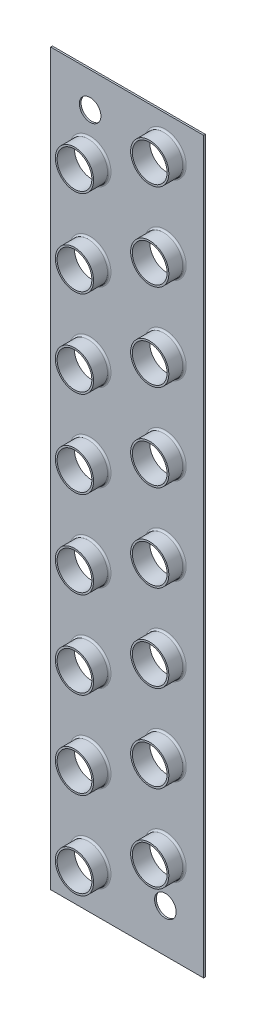
SolidWorks part; units mm, degrees
ref_plane "Front Plane" through (0, 0, 0) normal (0, 0, 1) x (1, 0, 0)
ref_plane "Top Plane" through (0, 0, 0) normal (0, 1, 0) x (1, 0, 0)
ref_plane "Right Plane" through (0, 0, 0) normal (1, 0, 0) x (0, 0, -1)
sketch "Sketch2" plane through (0, 0, 0) normal (0, 0, 1) x (1, 0, 0)
  line L1 (0, 0) -> (44, 0)
  line L2 (0, 0) -> (0, -210)
  line L3 (0, -210) -> (44, -210)
  line L4 (44, 0) -> (44, -210)
  dimension "D1" = 44
  dimension "D2" = 210
extrude "Boss-Extrude1" add sketch "Sketch2" along normal blind 0.5
sketch "Sketch3" plane through (0, 0, 0.5) normal (0, 0, 1) x (1, 0, 0)
  line L0 (44, 0) -> (0, 0) construction
  line L2 (11.3494, -22.5) -> (33, -22.5) construction
  line L3 (22.1747, -22.5) -> (22.1747, -34.2411) construction
  circle A0 centre (33, -10) radius 5
  circle A1 centre (11.3494, -22.5) radius 5
  point P11 (0, 0)
  point P12 (0, 0)
  point P13 (0, 0)
  point P14 (0, 0)
  dimension "D1" = 10
  dimension "D2" = 10
  dimension "D3" = 10
  dimension "D4" = 12.5
  dimension "D5" = 25
extrude "Cut-Extrude1" cut sketch "Sketch3" against normal through all
sketch "Sketch4" plane through (0, 0, 0.5) normal (0, 0, 1) x (1, 0, 0)
  circle A0 centre (11.3494, -22.5) radius 5.5
  circle A1 centre (11.3494, -22.5) radius 5
  circle A2 centre (11.3494, -22.5) radius 5
  circle A3 centre (33, -10) radius 5
  circle A4 centre (33, -10) radius 5
  circle A5 centre (33, -10) radius 5.5
  dimension "D1" = 0
  dimension "D2" = 0
  dimension "D3" = 0.5
extrude "Boss-Extrude2" add sketch "Sketch4" along normal blind 4.5
pattern_linear "LPattern1" count 8 spacing 25 along (0, -1, 0) of "Boss-Extrude2", "Cut-Extrude1"
fillet "Fillet1" radius 0.5 16 edges at (38.5, -10, 0.5) (16.8494, -22.5, 0.5) (38.5, -185, 0.5) (16.8494, -197.5, 0.5) (16.8494, -172.5, 0.5) (38.5, -160, 0.5) (16.8494, -147.5, 0.5) (38.5, -135, 0.5) (16.8494, -122.5, 0.5) (38.5, -110, 0.5) (16.8494, -97.5, 0.5) (38.5, -85, 0.5) (16.8494, -72.5, 0.5) (38.5, -60, 0.5) (38.5, -35, 0.5) (16.8494, -47.5, 0.5)
sketch "Sketch5" plane through (0, 0, 0) normal (0, 0, -1) x (-1, 0, 0)
  line L0 (-11.3494, -10) -> (-11.3494, -22.5) construction
  line L1 (-11.3494, -10) -> (-33, -10) construction
  line L2 (-33, -197.5) -> (-33, -185) construction
  line L3 (-11.3494, -197.5) -> (-33, -197.5) construction
  circle A1 centre (-33, -197.5) radius 3.1
  circle A2 centre (-11.3494, -10) radius 3.1
  dimension "D1" = 6.2
  dimension "D2" = 6.2
extrude "Cut-Extrude2" cut sketch "Sketch5" against normal through all
